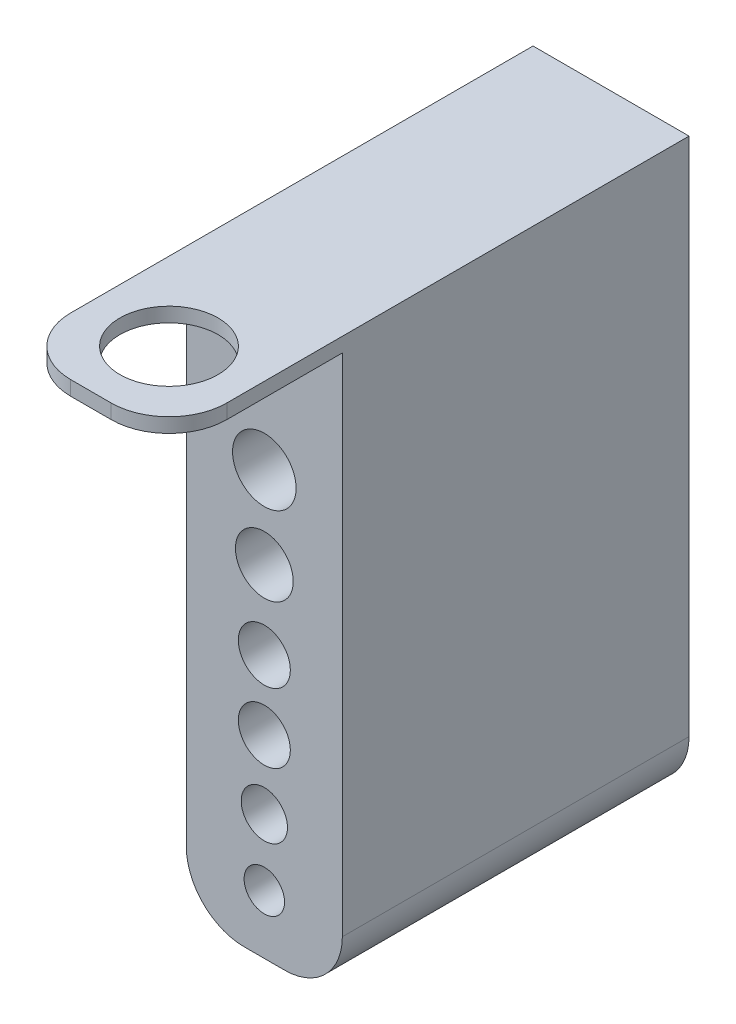
SolidWorks part; units mm, degrees
ref_plane "Front Plane" through (0, 0, 0) normal (0, 0, 1) x (1, 0, 0)
ref_plane "Top Plane" through (0, 0, 0) normal (0, 1, 0) x (1, 0, 0)
ref_plane "Right Plane" through (0, 0, 0) normal (1, 0, 0) x (0, 0, -1)
sketch "Sketch1" plane through (0, 0, 0) normal (0, 0, 1) x (1, 0, 0)
  line L1 (-13.5, 50) -> (13.5, 50)
  line L2 (-13.5, 50) -> (-13.5, -50)
  line L3 (-13.5, -50) -> (13.5, -50)
  line L4 (13.5, 50) -> (13.5, -50)
  line L5 (-13.5, 50) -> (13.5, -50) construction
  line L6 (-13.5, -50) -> (13.5, 50) construction
  point P0 (0, 0)
  dimension "D1" = 100
  dimension "D2" = 27
extrude "Boss-Extrude1" add sketch "Sketch1" along normal blind 60
fillet "Fillet1" radius 10 2 edges at (13.5, -50, 30) (-13.5, -50, 30)
sketch "Sketch2" plane through (0, 0, 60) normal (0, 0, 1) x (1, 0, 0)
  line L0 (13.5, -40) -> (13.5, 50) construction
  line L1 (-13.5, 50) -> (13.5, 50)
  line L2 (-13.5, 50) -> (-13.5, 47.5)
  line L3 (-13.5, 47.5) -> (13.5, 47.5)
  line L4 (13.5, 50) -> (13.5, 47.5)
  dimension "D1" = 2.5
extrude "Boss-Extrude2" add sketch "Sketch2" along normal blind 30
fillet "Fillet2" radius 10 2 edges at (-13.5, 48.75, 90) (13.5, 48.75, 90)
sketch "Sketch3" plane through (0, 47.5, 0) normal (0, -1, 0) x (1, 0, 0)
  line L0 (0, 90) -> (0, 76.5) construction
  line L1 (-3.5, 90) -> (3.5, 90) construction
  circle A0 centre (0, 76.5) radius 8.5
  dimension "D1" = 17
  dimension "D2" = 13.5
extrude "Cut-Extrude1" cut sketch "Sketch3" against normal through all
sketch "Sketch4" plane through (0, 0, 60) normal (0, 0, 1) x (1, 0, 0)
  line L0 (0, 23.2196) -> (0, -39.8149) construction
  circle A0 centre (0, 23.2196) radius 5.5
  circle A1 centre (0, 8.995) radius 5
  circle A2 centre (0, -4.5323) radius 4.5
  circle A3 centre (0, -16.5256) radius 4.5
  circle A4 centre (0, -28.3795) radius 4
  circle A5 centre (0, -39.8149) radius 3.5
  point P13 (0, -37.0411)
  point P14 (0, -23.392)
  point P15 (0, -8.7121)
  point P16 (0, -22.693)
  point P17 (0, 33.3649)
  point P18 (0, 18.9869)
  point P19 (0, 4.9496)
  point P20 (0, -39.8149)
  point P21 (0, 0)
  point P22 (0, -28.3795)
  point P23 (0, -16.5256)
  point P24 (0, -4.5323)
  point P25 (0, 8.995)
  point P26 (0, 23.2196)
  dimension "D1" = 11
  dimension "D2" = 10
  dimension "D3" = 9
  dimension "D4" = 9
  dimension "D5" = 8
  dimension "D6" = 7
extrude "Cut-Extrude2" cut sketch "Sketch4" against normal blind 57
